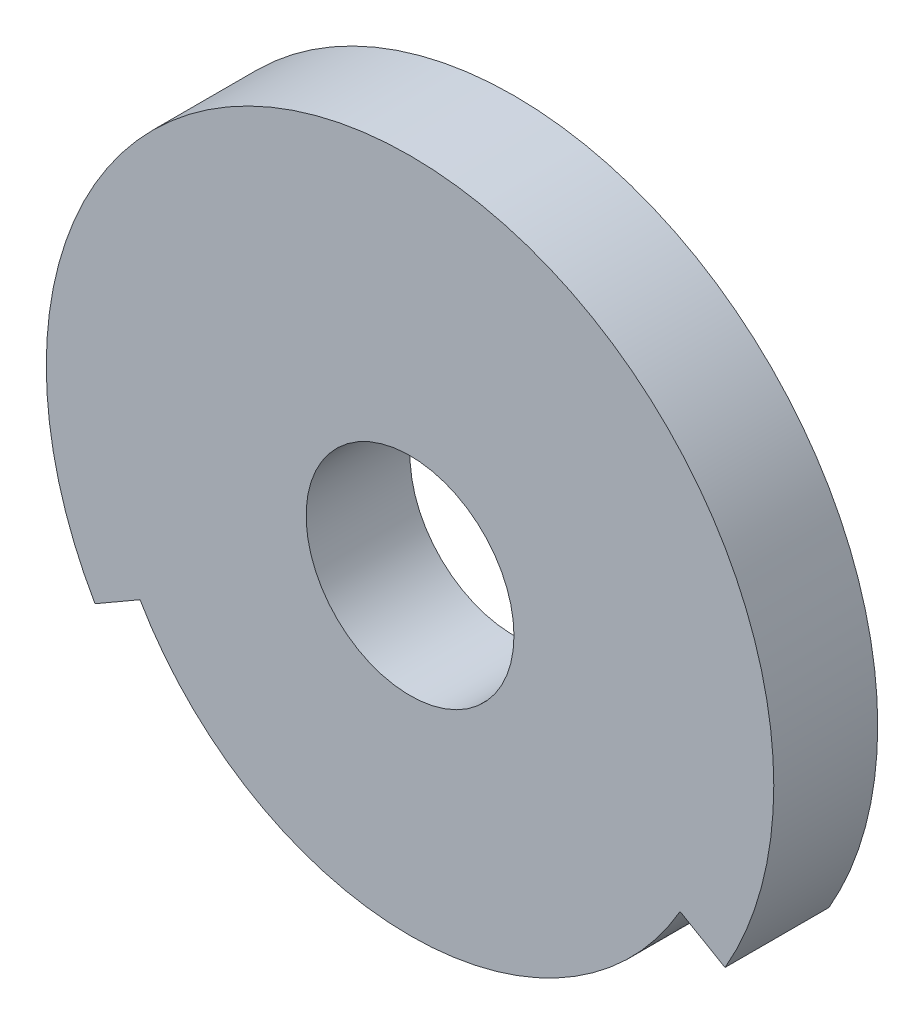
SolidWorks part; units mm, degrees
ref_plane "Front Plane" through (0, 0, 0) normal (0, 0, 1) x (1, 0, 0)
ref_plane "Top Plane" through (0, 0, 0) normal (0, 1, 0) x (1, 0, 0)
ref_plane "Right Plane" through (0, 0, 0) normal (1, 0, 0) x (0, 0, -1)
ref_plane "Plane1" through (0, 0, 0) normal (0, 0, -1) x (-1, 0, 0)
sketch "Sketch1" plane through (0, 0, 0) normal (0, 0, -1) x (-1, 0, 0)
  line L0 (-3.0311, -1.75) -> (-2.5981, -1.5)
  line L1 (2.5981, -1.5) -> (3.0311, -1.75)
  circle A0 centre (0, 0) radius 1
  arc A1 (-2.5981, -1.5) -> (2.5981, -1.5) centre (0, 0) ccw
  arc A2 (3.0311, -1.75) -> (-3.0311, -1.75) centre (0, 0) ccw
extrude "Boss-Extrude1" add sketch "Sketch1" against normal blind 1
